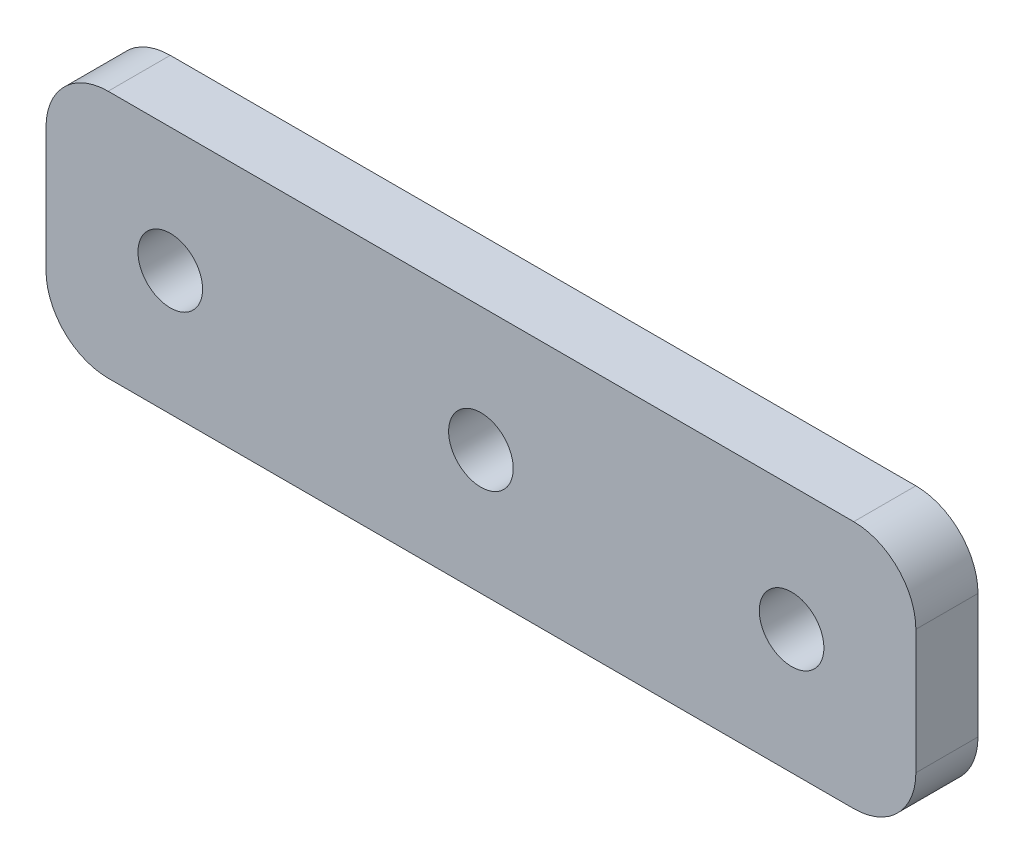
SolidWorks part; units mm, degrees
ref_plane "正面" through (0, 0, 0) normal (0, 0, 1) x (1, 0, 0)
ref_plane "平面" through (0, 0, 0) normal (0, 1, 0) x (1, 0, 0)
ref_plane "右側面" through (0, 0, 0) normal (1, 0, 0) x (0, 0, -1)
sketch "ｽｹｯﾁ2" plane through (0, 0, 0) normal (0, 0, 1) x (1, 0, 0)
  line L0 (0, 0) -> (25, 0) construction
  line L1 (25, 0) -> (50, 0) construction
  line L3 (60, -10) -> (-10, -10)
  line L4 (60, -10) -> (60, 10)
  line L5 (60, 10) -> (-10, 10)
  line L6 (-10, -10) -> (-10, 10)
  line L7 (60, -10) -> (-10, 10) construction
  line L8 (60, 10) -> (-10, -10) construction
  circle A0 centre (25, 0) radius 2.6
  circle A1 centre (50, 0) radius 2.6
  circle A2 centre (0, 0) radius 2.6
  dimension "D1" = 5.2
  dimension "D3" = 10
  dimension "D4" = 10
  dimension "D2" = 25
extrude "ﾎﾞｽ - 押し出し1" add sketch "ｽｹｯﾁ2" along normal blind 5
fillet "ﾌｨﾚｯﾄ1" radius 5 4 edges at (-10, -10, 2.5) (-10, 10, 2.5) (60, 10, 2.5) (60, -10, 2.5)
